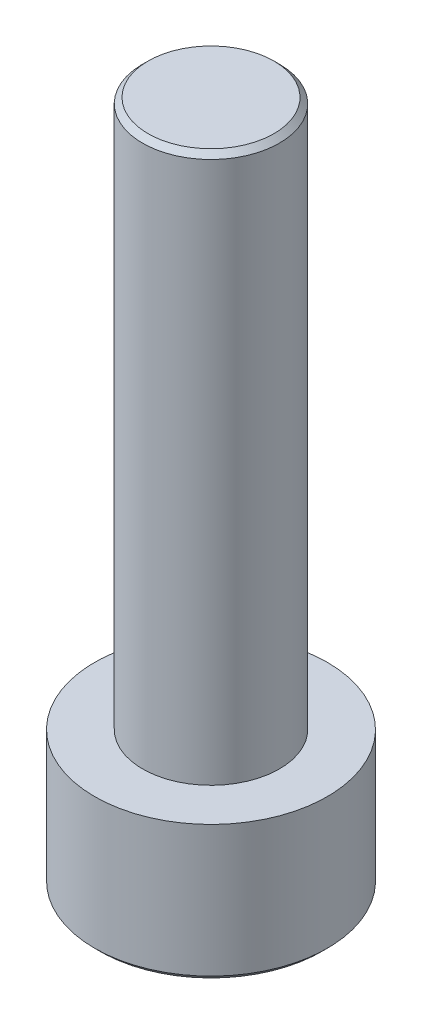
SolidWorks part; units mm, degrees
ref_plane "Front Plane" through (0, 0, 0) normal (0, 0, 1) x (1, 0, 0)
ref_plane "Top Plane" through (0, 0, 0) normal (0, 1, 0) x (1, 0, 0)
ref_plane "Right Plane" through (0, 0, 0) normal (1, 0, 0) x (0, 0, -1)
sketch "Reconstructed nominal axial profile" plane through (0, 0, 0) normal (0, 0, 1) x (1, 0, 0)
  line L0 (0, -500) -> (0, 50) construction
  line L1 (0, -5) -> (4.05, -5)
  line L2 (4.05, -5) -> (4.25, -4.8)
  line L3 (4.25, -4.8) -> (4.25, 0)
  line L4 (4.25, 0) -> (2.5, 0)
  line L5 (2.5, 0) -> (2.5, 19.8)
  line L6 (2.5, 19.8) -> (2.3, 20)
  line L7 (2.3, 20) -> (0, 20)
  line L8 (0, 20) -> (0, -5)
revolve "Native revolved geometry" add sketch "Reconstructed nominal axial profile" angle 360 about L0
sketch "Sketch2" plane through (0, 0, 0) normal (0, 1, 0) x (1, 0, 0)
  line L0 (2.3094, 0) -> (1.1547, -2)
  line L1 (1.1547, -2) -> (-1.1547, -2)
  line L2 (-1.1547, -2) -> (-2.3094, 0)
  line L3 (-2.3094, 0) -> (-1.1547, 2)
  line L4 (-1.1547, 2) -> (1.1547, 2)
  line L5 (1.1547, 2) -> (2.3094, 0)
extrude "Simplified nominal hex socket" cut sketch "Sketch2" along normal blind 2.5 from offset 5
